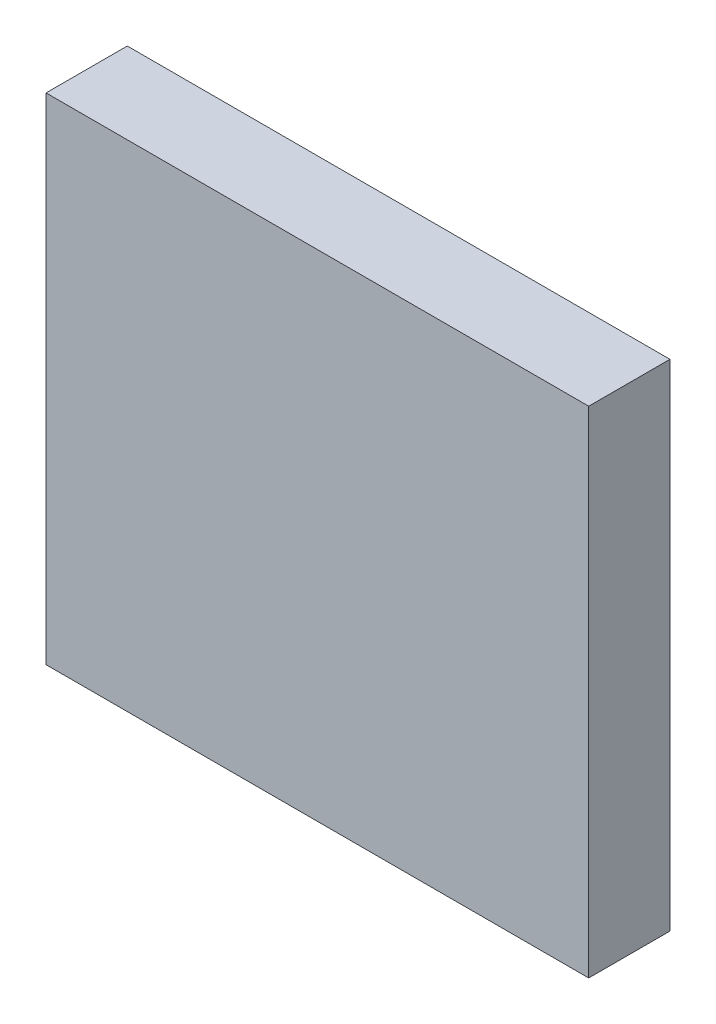
SolidWorks part; units mm, degrees
ref_plane "Ebene vorne" through (0, 0, 0) normal (0, 0, 1) x (1, 0, 0)
ref_plane "Ebene oben" through (0, 0, 0) normal (0, 1, 0) x (1, 0, 0)
ref_plane "Ebene rechts" through (0, 0, 0) normal (1, 0, 0) x (0, 0, -1)
sketch "Skizze1" plane through (0, 0, 0) normal (0, 0, 1) x (1, 0, 0)
  line L0 (-3.302, 3.048) -> (3.3782, 3.048)
  line L1 (3.3782, 3.048) -> (3.3782, -3.048)
  line L2 (3.3782, -3.048) -> (-3.302, -3.048)
  line L3 (-3.302, -3.048) -> (-3.302, 3.048)
extrude "Component_Outline" add sketch "Skizze1" along normal blind 1 separate body
sketch3d "3D-Skizze1"
  line L0 (0, 0, 0) -> (1, 0, 0)
  line L1 (0, 0, 0) -> (0, 1, 0)
  line L2 (0, 0, 0) -> (0, 0, 1)
  point P0 (0, 0, 0)
